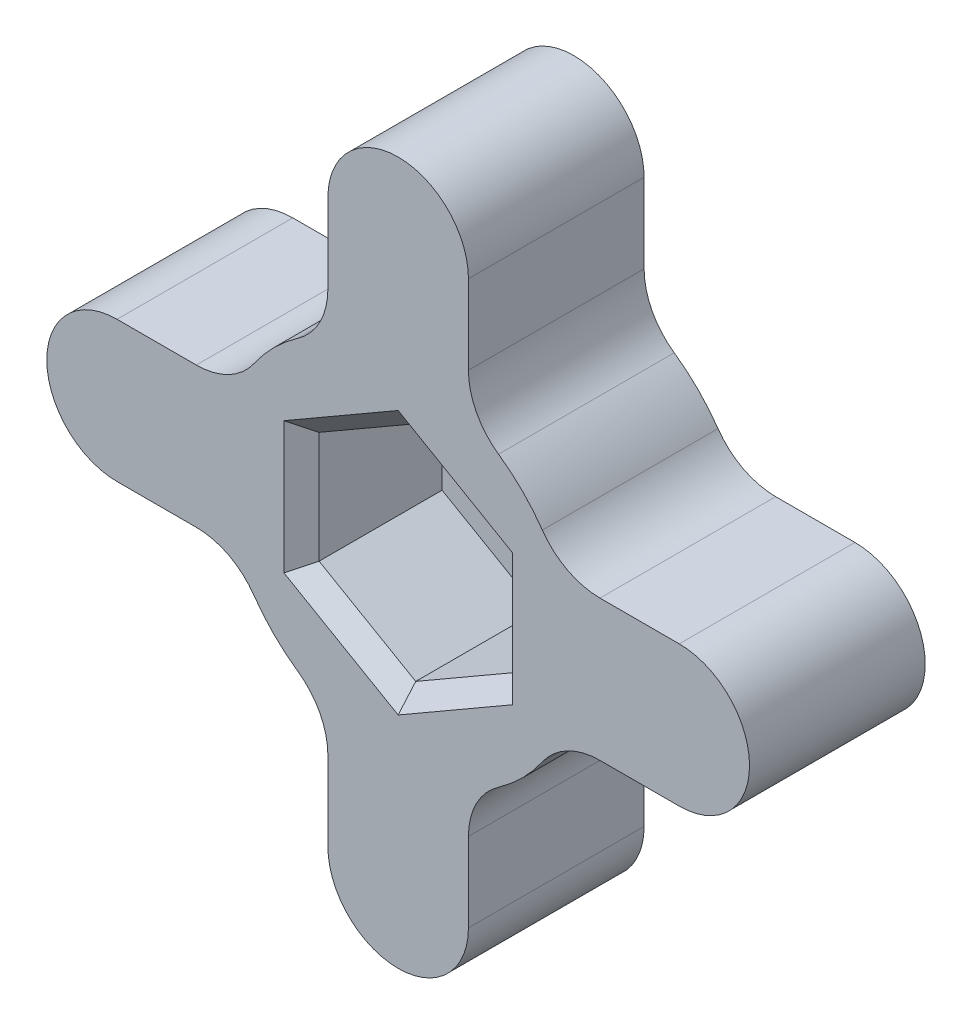
SolidWorks part; units mm, degrees
ref_plane "Plano frontal" through (0, 0, 0) normal (0, 0, 1) x (1, 0, 0)
ref_plane "Plano superior" through (0, 0, 0) normal (0, 1, 0) x (1, 0, 0)
ref_plane "Plano direito" through (0, 0, 0) normal (1, 0, 0) x (0, 0, -1)
sketch "Esboço1" plane through (0, 0, 0) normal (0, 0, 1) x (1, 0, 0)
  circle A0 centre (0, 0) radius 5
  dimension "D1" = 10
extrude "Ressalto-extrusão1" add sketch "Esboço1" along normal blind 5
sketch "Esboço2" plane through (0, 0, 5) normal (0, 0, 1) x (1, 0, 0)
  line L1 (0, 3.1754) -> (-2.75, 1.5877)
  line L2 (-2.75, 1.5877) -> (-2.75, -1.5877)
  line L3 (-2.75, -1.5877) -> (0, -3.1754)
  line L4 (0, -3.1754) -> (2.75, -1.5877)
  line L5 (2.75, -1.5877) -> (2.75, 1.5877)
  line L6 (2.75, 1.5877) -> (0, 3.1754)
  circle A0 centre (0, 0) radius 2.75 construction
  dimension "D1" = 5.5
extrude "Corte-extrusão1" cut sketch "Esboço2" against normal blind 4
sketch "Esboço3" plane through (0, 0, 1) normal (0, 0, 1) x (1, 0, 0)
  circle A0 centre (0, 0) radius 2
  dimension "D1" = 4
extrude "Corte-extrusão2" cut sketch "Esboço3" against normal through all
sketch "Esboço4" plane through (0, 0, 0) normal (0, 0, -1) x (-1, 0, 0)
  line L0 (0, 5) -> (0, -5) construction
  line L1 (-4.5826, 2) -> (-8, 2)
  line L3 (-4.5826, -2) -> (-8, -2)
  line L7 (2, 4.5826) -> (2, 8)
  line L8 (-2, 4.5826) -> (-2, 8)
  line L9 (4.5826, -2) -> (8, -2)
  line L10 (4.5826, 2) -> (8, 2)
  line L11 (-2, -4.5826) -> (-2, -8)
  line L12 (2, -4.5826) -> (2, -8)
  arc A0 (-8, 2) -> (-8, -2) centre (-8, 0) ccw
  circle A1 centre (0, 0) radius 2 construction
  arc A2 (-4.5826, 2) -> (-4.5826, -2) centre (0, 0) ccw
  circle A3 centre (0, 0) radius 5 construction
  arc A6 (2, 4.5826) -> (-2, 4.5826) centre (0, 0) ccw
  arc A7 (2, 8) -> (-2, 8) centre (0, 8) ccw
  arc A8 (4.5826, -2) -> (4.5826, 2) centre (0, 0) ccw
  arc A9 (8, -2) -> (8, 2) centre (8, 0) ccw
  arc A10 (-2, -4.5826) -> (2, -4.5826) centre (0, 0) ccw
  arc A11 (-2, -8) -> (2, -8) centre (0, -8) ccw
  point P32 (0, 0)
  dimension "D3" = 8
  dimension "D4" = 2
  dimension "D1" = 2
  dimension "D2" = 2
  dimension "D5" = 4
extrude "Ressalto-extrusão2" add sketch "Esboço4" against normal through all
chamfer "Chanfro1" distance 0.5 angle 45 6 edges at (1.375, 2.3816, 5) (2.75, 0, 5) (1.375, -2.3816, 5) (-1.375, -2.3816, 5) (-2.75, 0, 5) (-1.375, 2.3816, 5)
fillet "Filete1" radius 2 8 edges at (4.5826, -2, 2.5) (4.5826, 2, 2.5) (2, -4.5826, 2.5) (-2, -4.5826, 2.5) (-4.5826, -2, 2.5) (-4.5826, 2, 2.5) (-2, 4.5826, 2.5) (2, 4.5826, 2.5)
